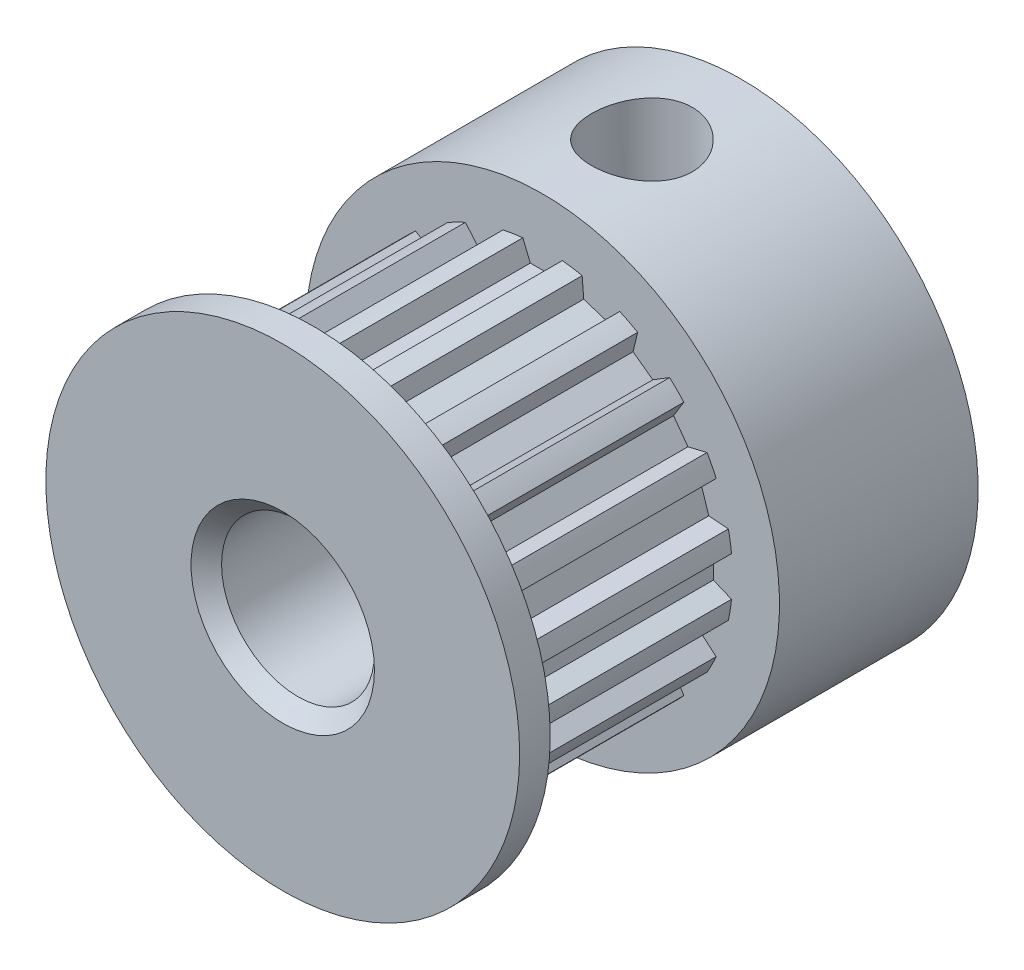
SolidWorks part; units mm, degrees
ref_plane "Alzado" through (0, 0, 0) normal (0, 0, 1) x (1, 0, 0)
ref_plane "Planta" through (0, 0, 0) normal (0, 1, 0) x (1, 0, 0)
ref_plane "Vista lateral" through (0, 0, 0) normal (1, 0, 0) x (0, 0, -1)
ref_plane "Plano1" through (0, 0, 0) normal (0, -1, 0) x (1, 0, 0)
sketch "Croquis1" plane through (0, 0, 0) normal (0, -1, 0) x (1, 0, 0)
  line L0 (7.75, 6.5) -> (0, 6.5)
  line L1 (0, 6.5) -> (0, 0)
  line L2 (0, 0) -> (7.75, 0)
  line L3 (7.75, 0) -> (7.75, 6.5)
  line L4 (0, 6.5) -> (0, 0) construction
revolve "Revolución1" add sketch "Croquis1" angle 360 about L4
sketch "Croquis2" plane through (0, 0, 6.5) normal (0, 0, 1) x (1, 0, 0)
  line L0 (5.1902, 2.107) -> (5.4374, 1.3461)
  line L1 (5.4374, 1.3461) -> (6.0784, 1.2957)
  line L2 (6.1813, 0.6461) -> (5.5872, 0.4)
  line L3 (5.5872, 0.4) -> (5.5872, -0.4)
  line L4 (5.5872, -0.4) -> (6.1813, -0.6461)
  line L5 (6.0784, -1.2957) -> (5.4374, -1.3461)
  line L6 (5.4374, -1.3461) -> (5.1902, -2.107)
  line L7 (5.1902, -2.107) -> (5.6791, -2.5246)
  line L8 (5.3806, -3.1106) -> (4.7553, -2.9605)
  line L9 (4.7553, -2.9605) -> (4.2851, -3.6077)
  line L10 (4.2851, -3.6077) -> (4.621, -4.156)
  line L11 (4.156, -4.621) -> (3.6077, -4.2851)
  line L12 (3.6077, -4.2851) -> (2.9605, -4.7553)
  line L13 (2.9605, -4.7553) -> (3.1106, -5.3806)
  line L14 (2.5246, -5.6791) -> (2.107, -5.1902)
  line L15 (2.107, -5.1902) -> (1.3461, -5.4374)
  line L16 (1.3461, -5.4374) -> (1.2957, -6.0784)
  line L17 (0.6461, -6.1813) -> (0.4, -5.5872)
  line L18 (0.4, -5.5872) -> (-0.4, -5.5872)
  line L19 (-0.4, -5.5872) -> (-0.6461, -6.1813)
  line L20 (-1.2957, -6.0784) -> (-1.3461, -5.4374)
  line L21 (-1.3461, -5.4374) -> (-2.107, -5.1902)
  line L22 (-2.107, -5.1902) -> (-2.5246, -5.6791)
  line L23 (-3.1106, -5.3806) -> (-2.9605, -4.7553)
  line L24 (-2.9605, -4.7553) -> (-3.6077, -4.2851)
  line L25 (-3.6077, -4.2851) -> (-4.156, -4.621)
  line L26 (-4.621, -4.156) -> (-4.2851, -3.6077)
  line L27 (-4.2851, -3.6077) -> (-4.7553, -2.9605)
  line L28 (-4.7553, -2.9605) -> (-5.3806, -3.1106)
  line L29 (-5.6791, -2.5246) -> (-5.1902, -2.107)
  line L30 (-5.1902, -2.107) -> (-5.4374, -1.3461)
  line L31 (-5.4374, -1.3461) -> (-6.0784, -1.2957)
  line L32 (-6.1813, -0.6461) -> (-5.5872, -0.4)
  line L33 (-5.5872, -0.4) -> (-5.5872, 0.4)
  line L34 (-5.5872, 0.4) -> (-6.1813, 0.6461)
  line L35 (-6.0784, 1.2957) -> (-5.4374, 1.3461)
  line L36 (-5.4374, 1.3461) -> (-5.1902, 2.107)
  line L37 (-5.1902, 2.107) -> (-5.6791, 2.5246)
  line L38 (-5.3806, 3.1106) -> (-4.7553, 2.9605)
  line L39 (-4.7553, 2.9605) -> (-4.2851, 3.6077)
  line L40 (-4.2851, 3.6077) -> (-4.621, 4.156)
  line L41 (-4.156, 4.621) -> (-3.6077, 4.2851)
  line L42 (-3.6077, 4.2851) -> (-2.9605, 4.7553)
  line L43 (-2.9605, 4.7553) -> (-3.1106, 5.3806)
  line L44 (-2.5246, 5.6791) -> (-2.107, 5.1902)
  line L45 (-2.107, 5.1902) -> (-1.3461, 5.4374)
  line L46 (-1.3461, 5.4374) -> (-1.2957, 6.0784)
  line L47 (-0.6461, 6.1813) -> (-0.4, 5.5872)
  line L48 (-0.4, 5.5872) -> (0.4, 5.5872)
  line L49 (0.4, 5.5872) -> (0.6461, 6.1813)
  line L50 (1.2957, 6.0784) -> (1.3461, 5.4374)
  line L51 (1.3461, 5.4374) -> (2.107, 5.1902)
  line L52 (2.107, 5.1902) -> (2.5246, 5.6791)
  line L53 (3.1106, 5.3806) -> (2.9605, 4.7553)
  line L54 (2.9605, 4.7553) -> (3.6077, 4.2851)
  line L55 (3.6077, 4.2851) -> (4.156, 4.621)
  line L56 (4.621, 4.156) -> (4.2851, 3.6077)
  line L57 (4.2851, 3.6077) -> (4.7553, 2.9605)
  line L58 (4.7553, 2.9605) -> (5.3806, 3.1106)
  line L59 (5.6791, 2.5246) -> (5.1902, 2.107)
  arc A0 (6.0784, 1.2957) -> (6.1813, 0.6461) centre (0, 0) cw
  arc A1 (6.1813, -0.6461) -> (6.0784, -1.2957) centre (0, 0) cw
  arc A2 (5.6791, -2.5246) -> (5.3806, -3.1106) centre (0, 0) cw
  arc A3 (4.621, -4.156) -> (4.156, -4.621) centre (0, 0) cw
  arc A4 (3.1106, -5.3806) -> (2.5246, -5.6791) centre (0, 0) cw
  arc A5 (1.2957, -6.0784) -> (0.6461, -6.1813) centre (0, 0) cw
  arc A6 (-0.6461, -6.1813) -> (-1.2957, -6.0784) centre (0, 0) cw
  arc A7 (-2.5246, -5.6791) -> (-3.1106, -5.3806) centre (0, 0) cw
  arc A8 (-4.156, -4.621) -> (-4.621, -4.156) centre (0, 0) cw
  arc A9 (-5.3806, -3.1106) -> (-5.6791, -2.5246) centre (0, 0) cw
  arc A10 (-6.0784, -1.2957) -> (-6.1813, -0.6461) centre (0, 0) cw
  arc A11 (-6.1813, 0.6461) -> (-6.0784, 1.2957) centre (0, 0) cw
  arc A12 (-5.6791, 2.5246) -> (-5.3806, 3.1106) centre (0, 0) cw
  arc A13 (-4.621, 4.156) -> (-4.156, 4.621) centre (0, 0) cw
  arc A14 (-3.1106, 5.3806) -> (-2.5246, 5.6791) centre (0, 0) cw
  arc A15 (-1.2957, 6.0784) -> (-0.6461, 6.1813) centre (0, 0) cw
  arc A16 (0.6461, 6.1813) -> (1.2957, 6.0784) centre (0, 0) cw
  arc A17 (2.5246, 5.6791) -> (3.1106, 5.3806) centre (0, 0) cw
  arc A18 (4.156, 4.621) -> (4.621, 4.156) centre (0, 0) cw
  arc A19 (5.3806, 3.1106) -> (5.6791, 2.5246) centre (0, 0) cw
extrude "Saliente-Extruir1" add sketch "Croquis2" along normal blind 7.5
ref_plane "Plano2" through (0, 0, 14) normal (0, 0, -1) x (-1, 0, 0)
sketch "Croquis3" plane through (0, 0, 14) normal (0, 0, -1) x (-1, 0, 0)
  circle A0 centre (0, 0) radius 7.75
extrude "Saliente-Extruir2" add sketch "Croquis3" against normal blind 1
hole_wizard "Diámetro de taladro Ø5.0 (5)1" positions "Croquis5" profile "Croquis4" hole size "Ø5.0" standard "Ansi Metric"
sketch "Croquis5" plane through (0, 0, 0) normal (0, 0, -1) x (-1, 0, 0)
  point P0 (0, 0)
sketch "Croquis4" plane through (0, 0, 0) normal (1, 0, 0) x (0, 1, 0)
  line L0 (0, 0) -> (0, 15)
  line L1 (0, 15) -> (2.5, 15)
  line L2 (2.5, 15) -> (2.5, 0)
  line L5 (2.5, 0) -> (0, 0)
  line L11 (0, -6.35) -> (0, 107.95) construction
  dimension "Diámetro de taladro hasta el siguiente" = 5
  dimension "Profundidad de taladro hasta el siguiente" = 15
hole_wizard "Taladro de margen para M3.51" positions "Croquis3D1" profile "Croquis6" hole size "M3.5" standard "Ansi Metric"
sketch3d "Croquis3D1"
  point P0 (0, 7.75, 3.25)
sketch "Croquis6" plane through (0, 7.75, 3.25) normal (1, 0, 0) x (0, 0, 1)
  line L0 (0, 0) -> (0, 5.25)
  line L1 (0, 5.25) -> (1.65, 5.25)
  line L2 (1.65, 5.25) -> (1.65, 0)
  line L5 (1.65, 0) -> (0, 0)
  line L11 (0, -6.35) -> (0, 107.95) construction
  dimension "Diámetro de taladro hasta el siguiente" = 3.3
  dimension "Profundidad de taladro hasta el siguiente" = 5.25
chamfer "Chaflán1" distance 0.5 angle 45 2 edges at (-2.5, 0, 15) (-2.5, 0, 0)
